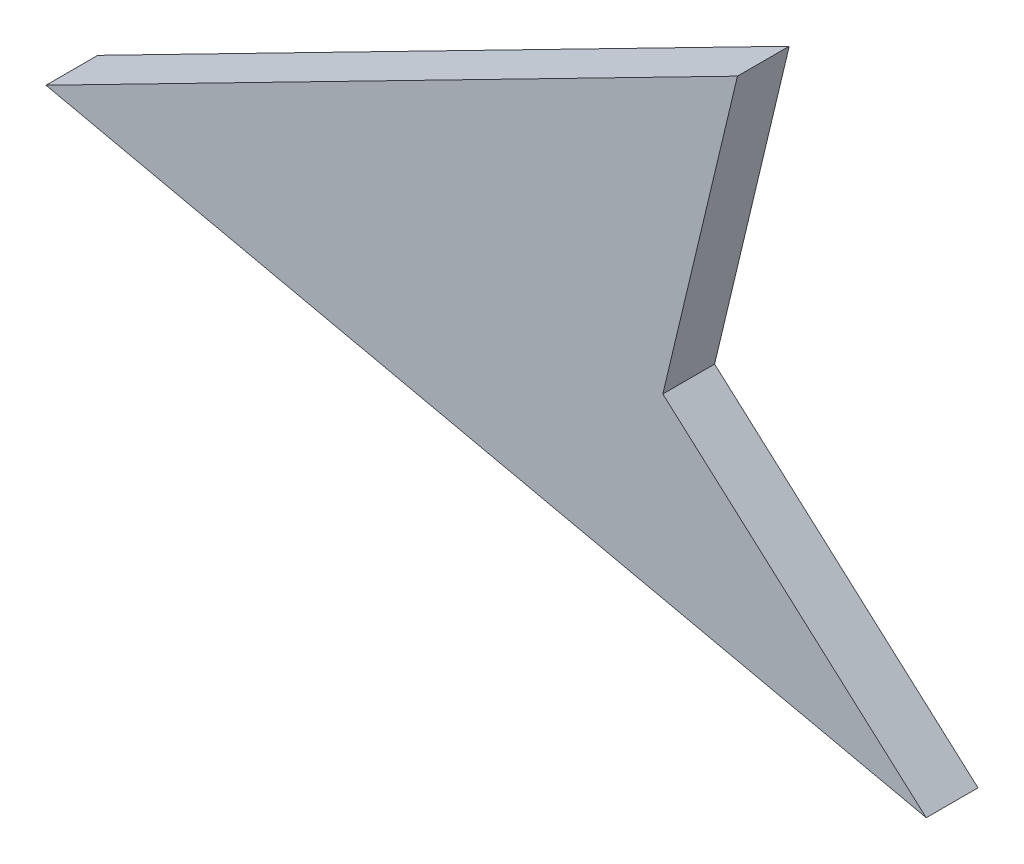
SolidWorks part; units mm, degrees
ref_plane "Front Plane" through (0, 0, 0) normal (0, 0, 1) x (1, 0, 0)
ref_plane "Top Plane" through (0, 0, 0) normal (0, 1, 0) x (1, 0, 0)
ref_plane "Right Plane" through (0, 0, 0) normal (1, 0, 0) x (0, 0, -1)
sketch "Sketch1" plane through (0, 0, 0) normal (0, 0, 1) x (1, 0, 0)
  line L0 (0, 0) -> (26.7101, 13.6591)
  line L1 (26.7101, 13.6591) -> (23.8273, 1.5842)
  line L2 (23.8273, 1.5842) -> (34.0022, -7.5046)
  line L3 (34.0022, -7.5046) -> (0, 0)
  point P4 (27.8577, 2.1271)
  point P6 (33.2902, -8.233)
  point P7 (23.8273, 1.5842)
  point P8 (34.0022, -7.5046)
extrude "Boss-Extrude1" add sketch "Sketch1" along normal blind 2
